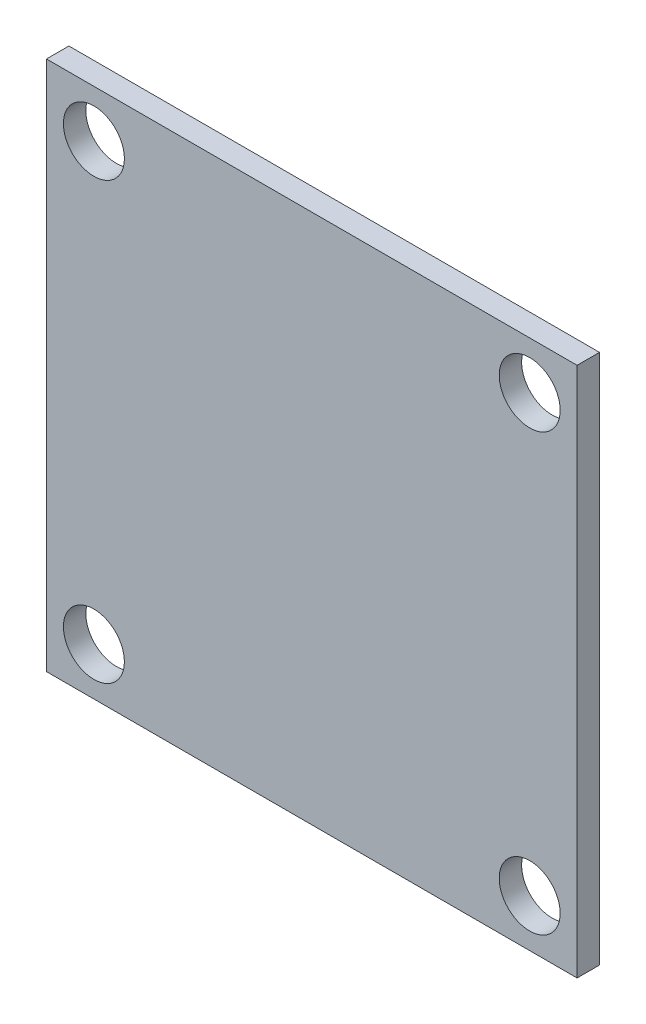
SolidWorks part; units mm, degrees
ref_plane "Front Plane" through (0, 0, 0) normal (0, 0, 1) x (1, 0, 0)
ref_plane "Top Plane" through (0, 0, 0) normal (0, 1, 0) x (1, 0, 0)
ref_plane "Right Plane" through (0, 0, 0) normal (1, 0, 0) x (0, 0, -1)
sketch "Sketch1" plane through (0, 0, 0) normal (0, 0, 1) x (1, 0, 0)
  line L1 (-14.2, 14.2) -> (14.2, 14.2)
  line L2 (-14.2, 14.2) -> (-14.2, -14.2)
  line L3 (-14.2, -14.2) -> (14.2, -14.2)
  line L4 (14.2, 14.2) -> (14.2, -14.2)
  line L5 (-14.2, 14.2) -> (14.2, -14.2) construction
  line L6 (-14.2, -14.2) -> (14.2, 14.2) construction
  point P0 (0, 0)
  dimension "D1" = 28.4
  dimension "D2" = 28.4
extrude "Boss-Extrude1" add sketch "Sketch1" along normal blind 1.2
hole_wizard "#4 Clearance Hole1" positions "Sketch3" profile "Sketch2" hole size "#4" standard "ANSI Inch" end condition through all
sketch "Sketch3" plane through (0, 0, 1.2) normal (0, 0, 1) x (1, 0, 0)
  line L0 (-14.2, 0) -> (14.2, 0) construction
  line L1 (-14.2, 14.2) -> (-14.2, -14.2) construction
  line L2 (14.2, -14.2) -> (14.2, 14.2) construction
  line L4 (0, 14.2) -> (0, -14.2) construction
  line L5 (14.2, 14.2) -> (-14.2, 14.2) construction
  line L6 (-14.2, -14.2) -> (14.2, -14.2) construction
  point P16 (-11.6625, 11.66)
  point P21 (-32.5597, 15.4639)
  point P22 (11.6625, 11.66)
  point P23 (-11.6625, -11.66)
  point P24 (11.6625, -11.66)
  dimension "D1" = 11.6625
sketch "Sketch2" plane through (-11.6625, 11.66, 1.2) normal (1, 0, 0) x (0, -1, 0)
  line L0 (0, 0) -> (0, 1.2)
  line L1 (0, 1.2) -> (1.6319, 1.2)
  line L2 (1.6319, 1.2) -> (1.6319, 0)
  line L5 (1.6319, 0) -> (0, 0)
  line L11 (0, -6.35) -> (0, 107.95) construction
  dimension "Thru Hole Dia." = 3.2639
  dimension "Thru Hole Depth" = 1.2
